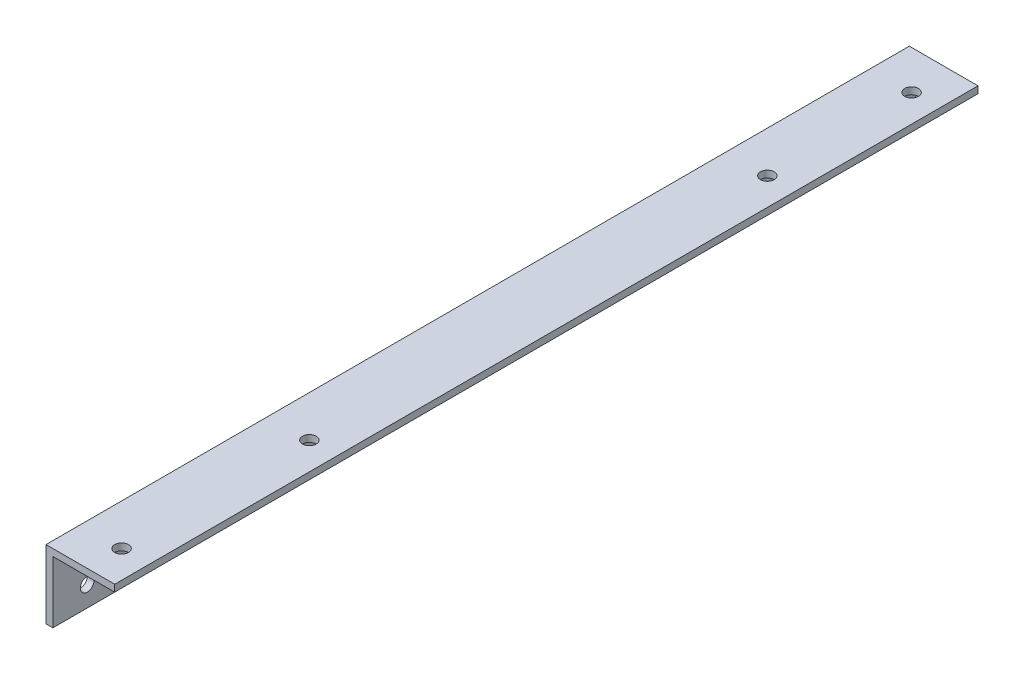
SolidWorks part; units mm, degrees
ref_plane "Plan de face" through (0, 0, 0) normal (0, 0, 1) x (1, 0, 0)
ref_plane "Plan de dessus" through (0, 0, 0) normal (0, 1, 0) x (1, 0, 0)
ref_plane "Plan de droite" through (0, 0, 0) normal (1, 0, 0) x (0, 0, -1)
sketch "Esquisse1" plane through (0, 0, 0) normal (0, 0, 1) x (1, 0, 0)
  line L0 (-19.4771, -9.6359) -> (-19.4771, -24.6359)
  line L1 (-17.9771, -11.1359) -> (-4.4771, -11.1359)
  line L2 (-4.4771, -11.1359) -> (-4.4771, -9.6359)
  line L3 (-4.4771, -9.6359) -> (-19.4771, -9.6359)
  line L4 (-19.4771, -24.6359) -> (-17.9771, -24.6359)
  line L5 (-17.9771, -24.6359) -> (-17.9771, -11.1359)
  dimension "D1" = 15
  dimension "D2" = 1.5
  dimension "D4" = 15
extrude "Extrusion1" add sketch "Esquisse1" along normal blind 188.5
sketch "Esquisse2" plane through (0, -9.6359, 0) normal (0, 1, 0) x (-1, 0, 0)
  line L0 (10.4771, 195.5) -> (10.4771, 8.5) construction
  line L1 (4.4771, 188.5) -> (4.4771, 0) construction
  line L2 (4.4771, 0) -> (19.4771, 0) construction
  line L4 (17.9771, 188.5) -> (4.4771, 188.5) construction
  line L6 (4.4771, 188.5) -> (4.4771, 0) construction
  circle A1 centre (10.4771, 8.5) radius 1.5
  circle A2 centre (10.4771, 181) radius 1.5
  circle A3 centre (10.4771, 140) radius 1.5
  circle A4 centre (10.4771, 40) radius 1.5
  dimension "D4" = 6
  dimension "D6" = 140
  dimension "D2" = 8.5
  dimension "D3" = 7.5
  dimension "D7" = 40
  dimension "D8" = 6
  dimension "D9" = 6
  dimension "D12" = 6
extrude "Extrusion2" cut sketch "Esquisse2" against normal blind 267
sketch "Esquisse3" plane through (-17.9771, 0, 0) normal (1, 0, 0) x (0, 0, -1)
  line L0 (-188.5, -24.6359) -> (0, -24.6359) construction
  line L1 (0, -24.6359) -> (0, -11.1359) construction
  line L2 (-188.5, -24.6359) -> (-188.5, -11.1359) construction
  circle A0 centre (-40, -20.1359) radius 1.5
  circle A1 centre (-140, -20.1359) radius 1.5
  circle A2 centre (-181, -20.1359) radius 1.5
  circle A3 centre (-7.5, -17.1359) radius 1.7231
  dimension "D1" = 4.5
  dimension "D5" = 7.5
  dimension "D2" = 4.5
  dimension "D3" = 40
  dimension "D4" = 140
  dimension "D6" = 4.5
  dimension "D7" = 7.5
  dimension "D8" = 7.5
extrude "Extrusion3" cut sketch "Esquisse3" against normal blind 10
